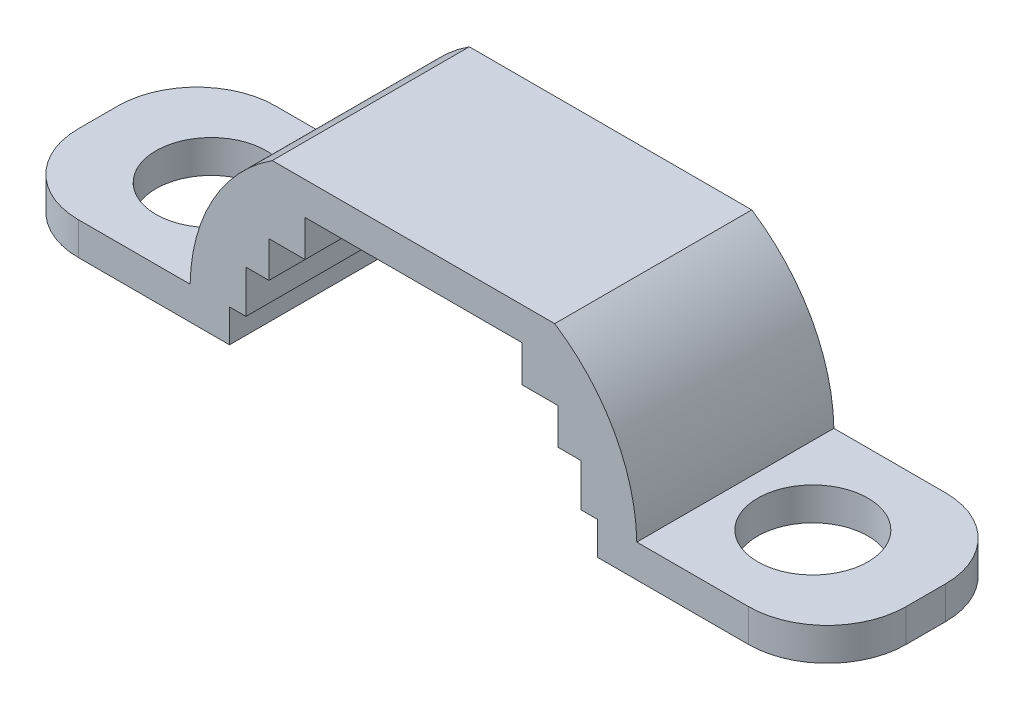
SolidWorks part; units mm, degrees
material "PLA"
ref_plane "Front Plane" through (0, 0, 0) normal (0, 0, 1) x (1, 0, 0)
ref_plane "Top Plane" through (0, 0, 0) normal (0, 1, 0) x (1, 0, 0)
ref_plane "Right Plane" through (0, 0, 0) normal (1, 0, 0) x (0, 0, -1)
sketch "Sketch1" plane through (0, 0, 0) normal (0, 0, 1) x (1, 0, 0)
  line L0 (-63, 4.5) -> (-28, 4.5)
  line L1 (-28, 4.5) -> (-28, 9.5)
  line L2 (-28, 9.5) -> (-25.5, 9.5)
  line L3 (-25.5, 9.5) -> (-25.5, 16)
  line L4 (-25.5, 16) -> (-22, 16)
  line L5 (-22, 16) -> (-22, 21.5)
  line L6 (-22, 21.5) -> (-16.5, 21.5)
  line L7 (-16.5, 21.5) -> (-16.5, 27.05)
  line L8 (-16.5, 27.05) -> (0, 27.05)
  circle A0 centre (0, 0) radius 27.05
  dimension "D1" = 54.1
  dimension "D2" = 35
  dimension "D3" = 4.5
  dimension "D4" = 28
  dimension "D5" = 5
  dimension "D6" = 2.5
  dimension "D7" = 6.5
  dimension "D8" = 3.5
  dimension "D9" = 5.5
  dimension "D10" = 5.5
  dimension "D11" = 16.5
  dimension "D12" = 5.55
extrude "Extrude-Thin1" add sketch "Sketch1" along normal mid plane 30 thin contours L0 L1 L2 L3 L4 L5 L6 L7 L8
sketch "Sketch2" plane through (0, 9.5, 0) normal (0, 1, 0) x (1, 0, 0)
  line L0 (0, -15) -> (0, 15) construction
  circle A0 centre (-45.8, 0) radius 8.4
  dimension "D1" = 16.8
  dimension "D2" = 45.8
extrude "Cut-Extrude1" cut sketch "Sketch2" against normal through all
fillet "Fillet1" radius 12 2 edges at (-63, 7, -15) (-63, 7, 15)
mirror "Mirror1" about plane through (0, 32.05, 15) normal (1, 0, 0) of "Fillet1", "Cut-Extrude1", "Extrude-Thin1"
sketch "Sketch4" plane through (0, 0, -15) normal (0, 0, -1) x (-1, 0, 0)
  line L0 (-51, 9.5) -> (-33, 9.5) construction
  line L1 (-51, 9.5) -> (-51, 4.5) construction
  line L3 (-34, 9.5) -> (-33, 9.5)
  line L4 (-33, 9.5) -> (-33, 14.5) construction
  line L5 (-33, 9.5) -> (-33, 14.5)
  line L6 (-21.5, 26.5) -> (-21.5, 32.05) construction
  line L7 (-27, 26.5) -> (-21.5, 26.5) construction
  line L8 (-27, 21) -> (-27, 26.5) construction
  line L9 (-30.5, 21) -> (-27, 21) construction
  line L10 (-30.5, 14.5) -> (-30.5, 21) construction
  line L11 (-33, 14.5) -> (-30.5, 14.5) construction
  line L12 (-21.5, 26.5) -> (-21.5, 32.05)
  line L13 (-27, 26.5) -> (-21.5, 26.5)
  line L14 (-27, 21) -> (-27, 26.5)
  line L15 (-30.5, 21) -> (-27, 21)
  line L16 (-30.5, 14.5) -> (-30.5, 21)
  line L17 (-33, 14.5) -> (-30.5, 14.5)
  arc A0 (-34, 9.5) -> (-21.5, 32.05) centre (-6.5046, 8.9982) cw
  dimension "D1" = 27.5
  dimension "D2" = 17
extrude "Boss-Extrude1" add sketch "Sketch4" against normal up to surface (30 mm away)
mirror "Mirror2" about plane through (0, 0, 0) normal (1, 0, 0) of "Boss-Extrude1"
